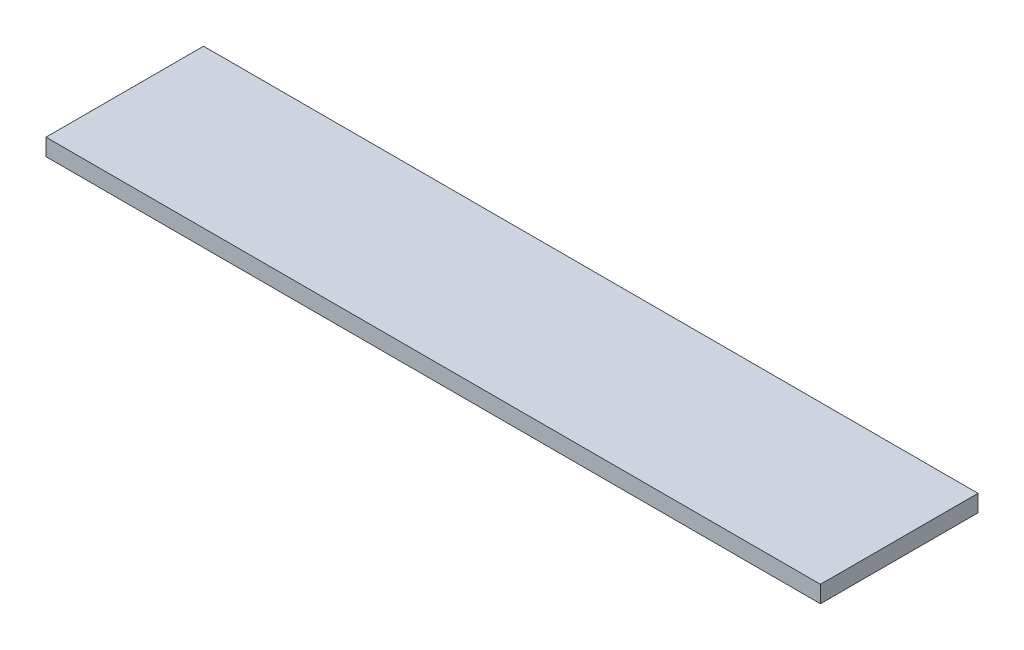
SolidWorks part; units mm, degrees
ref_plane "Front Plane" through (0, 0, 0) normal (0, 0, 1) x (1, 0, 0)
ref_plane "Top Plane" through (0, 0, 0) normal (0, 1, 0) x (1, 0, 0)
ref_plane "Right Plane" through (0, 0, 0) normal (1, 0, 0) x (0, 0, -1)
sketch "Sketch1" plane through (0, 0, 0) normal (0, 1, 0) x (1, 0, 0)
  line L0 (-81.7095, 26.9285) -> (193.1584, 26.9285)
  line L1 (193.1584, 26.9285) -> (193.1584, -28.9897)
  line L2 (193.1584, -28.9897) -> (-81.7095, -28.9897)
  line L3 (-81.7095, -28.9897) -> (-81.7095, 26.9285)
  point P4 (-81.7095, 26.9285)
  point P6 (193.1584, 26.9285)
  point P7 (-81.7095, 26.9285)
extrude "Boss-Extrude1" add sketch "Sketch1" along normal blind 6
